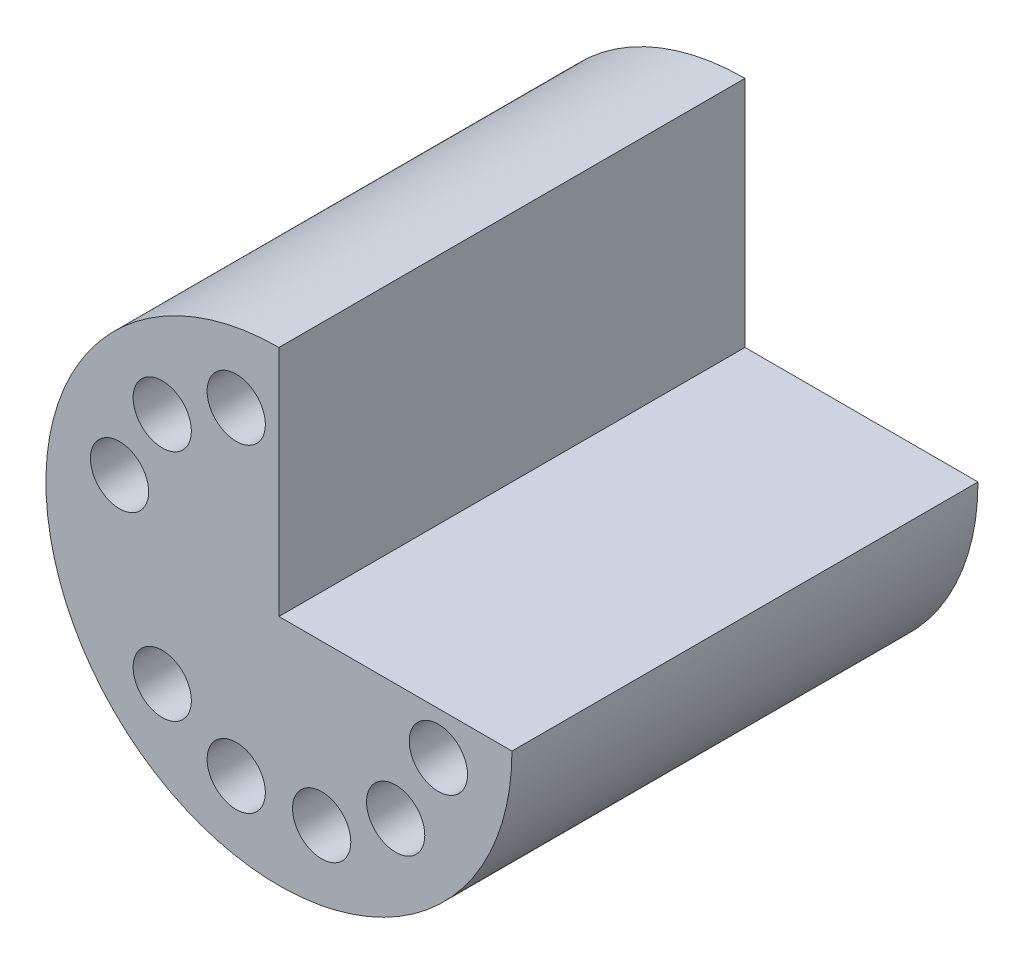
SolidWorks part; units mm, degrees
ref_plane "Front Plane" through (0, 0, 0) normal (0, 0, 1) x (1, 0, 0)
ref_plane "Top Plane" through (0, 0, 0) normal (0, 1, 0) x (1, 0, 0)
ref_plane "Right Plane" through (0, 0, 0) normal (1, 0, 0) x (0, 0, -1)
sketch "Sketch1" plane through (0, 0, 0) normal (0, 0, 1) x (1, 0, 0)
  line L0 (0, 76.2) -> (0, 0)
  line L1 (0, 0) -> (76.2, 0)
  arc A0 (0, 76.2) -> (76.2, 0) centre (0, 0) ccw
  dimension "D1" = 76.2
extrude "Boss-Extrude1" add sketch "Sketch1" against normal blind 152.4
sketch "Sketch2" plane through (0, 0, 0) normal (0, 0, 1) x (1, 0, 0)
  line L0 (0, 0) -> (-13.9698, 52.1358) construction
  line L1 (0, 0) -> (0, 76.2) construction
  circle A0 centre (-13.9698, 52.1358) radius 9.525
  circle A1 centre (0, 0) radius 53.975 construction
  dimension "D1" = 107.95
  dimension "D2" = 19.05
  dimension "D3" = 15
extrude "Cut-Extrude1" cut sketch "Sketch2" against normal through all
pattern_circular "CirPattern1" count 9 every 30 about axis through (0, 0, 0) along (0, 0, 1) skipping 3 of "Cut-Extrude1"
